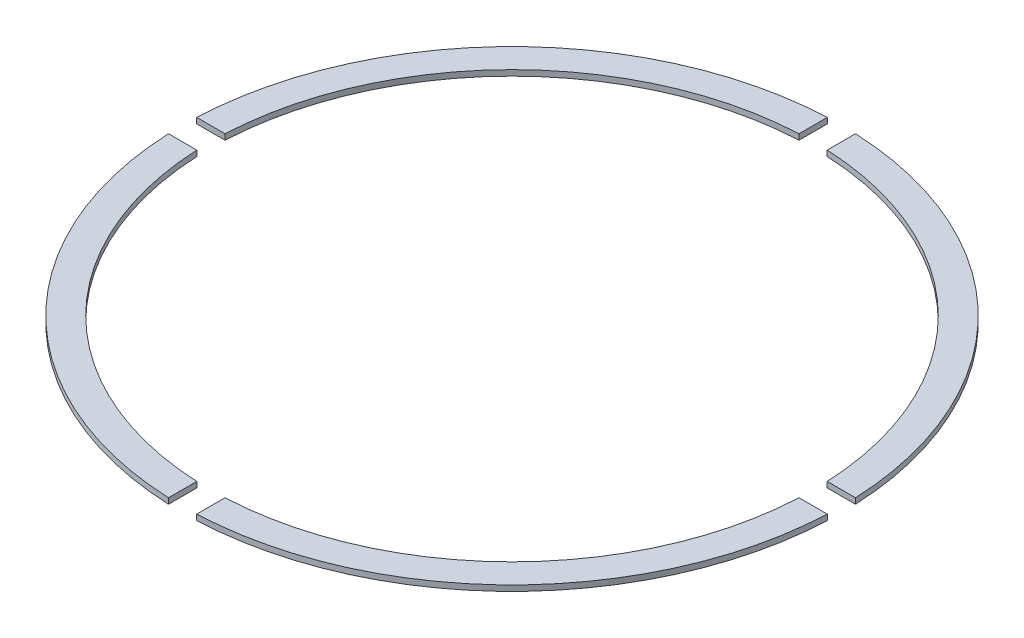
SolidWorks part; units mm, degrees
ref_plane "Front Plane" through (0, 0, 0) normal (0, 0, 1) x (1, 0, 0)
ref_plane "Top Plane" through (0, 0, 0) normal (0, 1, 0) x (1, 0, 0)
ref_plane "Right Plane" through (0, 0, 0) normal (1, 0, 0) x (0, 0, -1)
sketch "Sketch1" plane through (0, 0, 0) normal (0, 1, 0) x (1, 0, 0)
  line L0 (-160, 0) -> (160, 0) construction
  circle A0 centre (0, 0) radius 160
  circle A1 centre (0, 0) radius 175
  dimension "D1" = 320
  dimension "D2" = 350
extrude "Boss-Extrude1" add sketch "Sketch1" along normal mid plane 3
sketch "Sketch2" plane through (0, 0, 0) normal (0, 1, 0) x (1, 0, 0)
  line L0 (-175, 0) -> (175, 0) construction
  line L1 (0, 175) -> (0, -175) construction
  line L3 (183.8046, 7.5) -> (151.1954, 7.5)
  line L4 (183.8046, 7.5) -> (183.8046, -7.5)
  line L5 (183.8046, -7.5) -> (151.1954, -7.5)
  line L6 (151.1954, 7.5) -> (151.1954, -7.5)
  line L7 (183.8046, 7.5) -> (151.1954, -7.5) construction
  line L8 (183.8046, -7.5) -> (151.1954, 7.5) construction
  circle A0 centre (0, 0) radius 175 construction
  circle A1 centre (0, 0) radius 167.5 construction
  circle A2 centre (0, 0) radius 160 construction
  point P7 (167.5, 0)
  dimension "D2" = 7.5
  dimension "D1" = 15
extrude "axis gap" cut sketch "Sketch2" against normal through all both and the other way through all
sketch "Sketch3" plane through (0, 0, 0) normal (0, 0, 1) x (1, 0, 0)
  line L0 (0, -250) -> (0, 250) construction
  dimension "D1" = 500
pattern_circular "CirPattern1" count 4 every 90 about axis through (0, 0, 0) along (0, 1, 0) of "axis gap"
